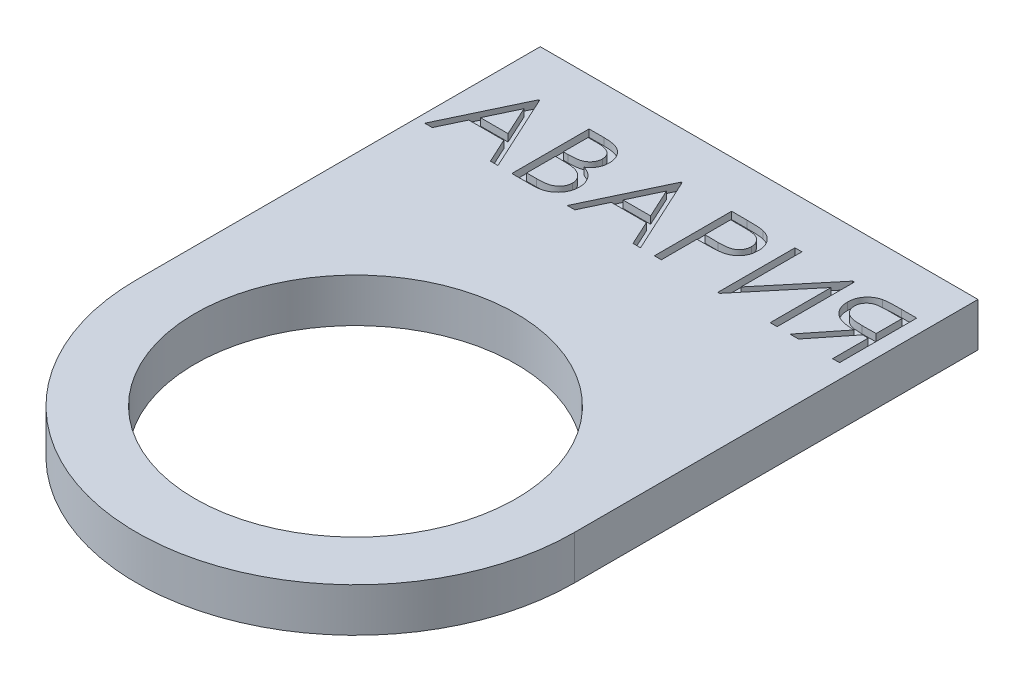
SolidWorks part; units mm, degrees
ref_plane "Front Plane" through (0, 0, 0) normal (0, 0, 1) x (1, 0, 0)
ref_plane "Top Plane" through (0, 0, 0) normal (0, 1, 0) x (1, 0, 0)
ref_plane "Right Plane" through (0, 0, 0) normal (1, 0, 0) x (0, 0, -1)
sketch "Sketch1" plane through (0, 0, 0) normal (0, 1, 0) x (1, 0, 0)
  line L0 (-19.7525, -10.1623) -> (19.1814, -10.1623) construction
  line L1 (15, 17.5) -> (-15, 17.5)
  line L2 (15, 17.5) -> (15, -10.1623)
  line L4 (-15, 17.5) -> (-15, -10.1623)
  line L5 (0, 15.6015) -> (0, -29.3739) construction
  line L6 (-18.6113, 0) -> (19.987, 0) construction
  arc A0 (-15, -10.1623) -> (15, -10.1623) centre (0, -10.1623) ccw
  circle A1 centre (0, -10.1623) radius 11
  point P0 (0, 0)
  dimension "D1" = 22
  dimension "D3" = 15
  dimension "D2" = 17.5
extrude "Boss-Extrude1" add sketch "Sketch1" along normal mid plane 3
sketch "Sketch2" plane through (0, 1.5, 0) normal (0, 1, 0) x (1, 0, 0)
  line L0 (15, 9) -> (-15, 9) construction
  line L1 (-15, 17.5) -> (-15, -10.1623) construction
  line L2 (15, 17.5) -> (-15, 17.5) construction
  line L3 (15, -10.1623) -> (15, 17.5) construction
  text T0 "АВАРИЯ" font "Century Gothic" height in points 20
  dimension "D1" = 8.5
extrude "Cut-Extrude1" cut sketch "Sketch2" against normal blind 0.5
